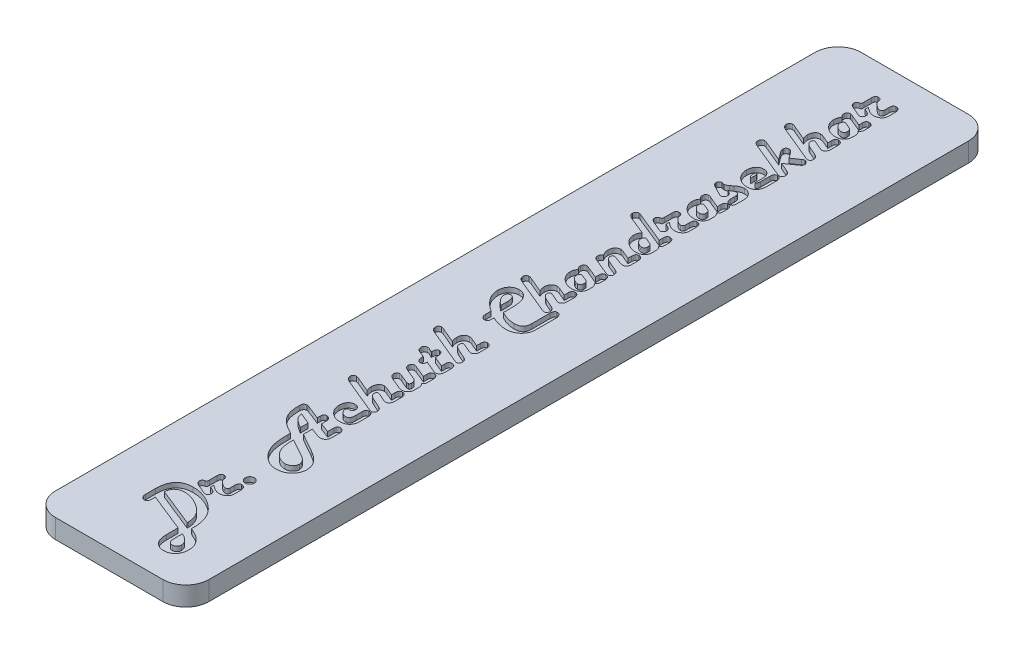
SolidWorks part; units mm, degrees
ref_plane "Front Plane" through (0, 0, 0) normal (0, 0, 1) x (1, 0, 0)
ref_plane "Top Plane" through (0, 0, 0) normal (0, 1, 0) x (1, 0, 0)
ref_plane "Right Plane" through (0, 0, 0) normal (1, 0, 0) x (0, 0, -1)
sketch "Sketch1" plane through (0, 0, 0) normal (0, 0, 1) x (1, 0, 0)
  line L0 (0, 1.5875) -> (0, -1.5875)
  line L1 (-12.7, 0) -> (12.7, 0) construction
  point P6 (0, 0)
  dimension "Width" = 25.4
  dimension "Thk" = 3.175
sketch "Sketch2" plane through (0, 0, 0) normal (1, 0, 0) x (0, 0, -1)
  line L0 (66.675, 0) -> (-66.675, 0)
  point P4 (0, 0)
  dimension "Length" = 133.35
sketch "Sketch3" plane through (0, 0, 0) normal (0, 0, 1) x (1, 0, 0)
  line L1 (12.7, 1.5875) -> (-12.7, 1.5875)
  line L2 (12.7, 1.5875) -> (12.7, -1.5875)
  line L3 (12.7, -1.5875) -> (-12.7, -1.5875)
  line L4 (-12.7, 1.5875) -> (-12.7, -1.5875)
  line L5 (12.7, 1.5875) -> (-12.7, -1.5875) construction
  line L6 (12.7, -1.5875) -> (-12.7, 1.5875) construction
  point P0 (0, 0)
extrude "Boss-Extrude1" add sketch "Sketch3" along normal up to vertex (66.675 mm away) and the other way up to vertex (66.675 mm away) up to point (0, 0, 66.675) other way up to point (0, 0, -66.675)
sketch "Sketch5" plane through (0, 1.5875, 0) normal (0, 1, 0) x (1, 0, 0)
  line L2 (9.652, -66.675) -> (-9.398, -66.675) construction
  line L3 (-12.7, -63.5025) -> (-12.7, 63.627) construction
  line L12 (12.7, -66.675) -> (12.7, 66.675)
  line L13 (12.7, 66.675) -> (-12.7, 66.675)
  line L14 (-12.7, 66.675) -> (-12.7, -66.675)
  line L15 (-12.7, -66.675) -> (12.7, -66.675)
  line L16 (12.7, -62.865) -> (12.7, 62.865)
  line L17 (8.89, 66.675) -> (-8.89, 66.675)
  line L18 (-12.7, 62.865) -> (-12.7, -62.865)
  line L19 (-8.89, -66.675) -> (8.89, -66.675)
  arc A8 (12.7, 62.865) -> (8.89, 66.675) centre (8.89, 62.865) ccw
  arc A9 (-8.89, 66.675) -> (-12.7, 62.865) centre (-8.89, 62.865) ccw
  arc A10 (12.7, -62.865) -> (8.89, -66.675) centre (8.89, -62.865) cw
  arc A11 (-8.89, -66.675) -> (-12.7, -62.865) centre (-8.89, -62.865) cw
  dimension "D2" = 3.81
  dimension "D1" = 0
extrude "Cut-Extrude2" cut sketch "Sketch5" against normal through all flip side to cut
sketch "Sketch4" plane through (0, 1.5875, 0) normal (0, 1, 0) x (1, 0, 0)
  line L0 (0, 0) -> (2.54, 0) construction
  line L1 (2.54, -66.675) -> (2.54, 66.675) construction
  line L2 (8.89, 66.675) -> (-8.89, 66.675) construction
  text T0 "Dr. Achuth Chandrasekhar\r\n" font "Harlow Solid Italic" height in points 24
  point P8 (2.54, 0)
  dimension "D1" = 2.54
extrude "Cut-Extrude1" cut sketch "Sketch4" against normal blind 0.7937
